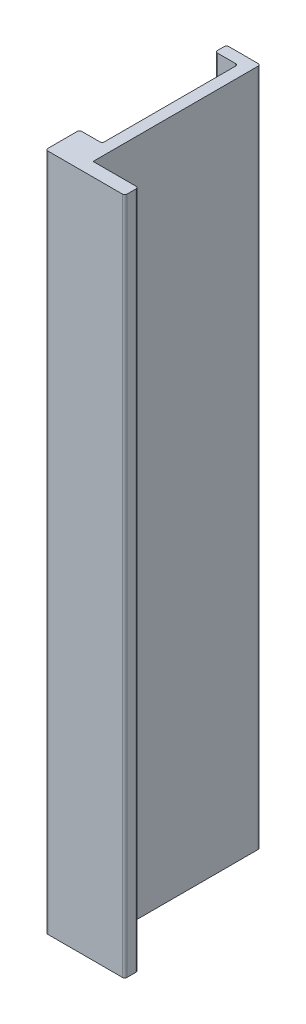
SolidWorks part; units mm, degrees
ref_plane "Front Plane" through (0, 0, 0) normal (1, 0, 0) x (0, 1, 0)
ref_plane "Top Plane" through (0, 0, 0) normal (0, 0, 1) x (0, 1, 0)
ref_plane "Right Plane" through (0, 0, 0) normal (0, 1, 0) x (-1, 0, 0)
sketch "Sketch1" plane through (0, 0, 0) normal (1, 0, 0) x (0, 1, 0)
  line L1 (0, 0) -> (300, 0)
  line L2 (0, 0) -> (0, -80)
  line L3 (0, -80) -> (300, -80)
  line L4 (300, 0) -> (300, -80)
  dimension "D1" = 80
  dimension "D2" = 300
extrude "Boss-Extrude1" add sketch "Sketch1" along normal blind 15
sketch "Sketch2" plane through (15, 0, 0) normal (1, 0, 0) x (0, 1, 0)
  line L0 (300, -80) -> (300, 0) construction
  line L1 (0, 0) -> (300, 0)
  line L2 (0, 0) -> (0, -6)
  line L3 (0, -6) -> (300, -6)
  line L4 (300, 0) -> (300, -6)
  dimension "D1" = 6
extrude "Boss-Extrude2" add sketch "Sketch2" along normal blind 20
sketch "Sketch3" plane through (0, 0, 0) normal (-1, 0, 0) x (0, -1, 0)
  line L0 (-300, -80) -> (-300, 0) construction
  line L1 (-300, -15) -> (0, -15)
  line L2 (-300, -15) -> (-300, -75)
  line L3 (-300, -75) -> (0, -75)
  line L4 (0, -15) -> (0, -75)
  line L5 (0, 0) -> (0, -80) construction
  line L6 (0, -80) -> (-300, -80) construction
  dimension "D1" = 5
  dimension "D2" = 60
extrude "Cut-Extrude1" cut sketch "Sketch3" against normal blind 10
fillet "Fillet1" radius 1 9 edges at (15, 150, -80) (35, 150, 0) (35, 150, -6) (0, 150, 0) (10, 150, -15) (0, 150, -80) (0, 150, -75) (10, 150, -75) (0, 150, -15)
